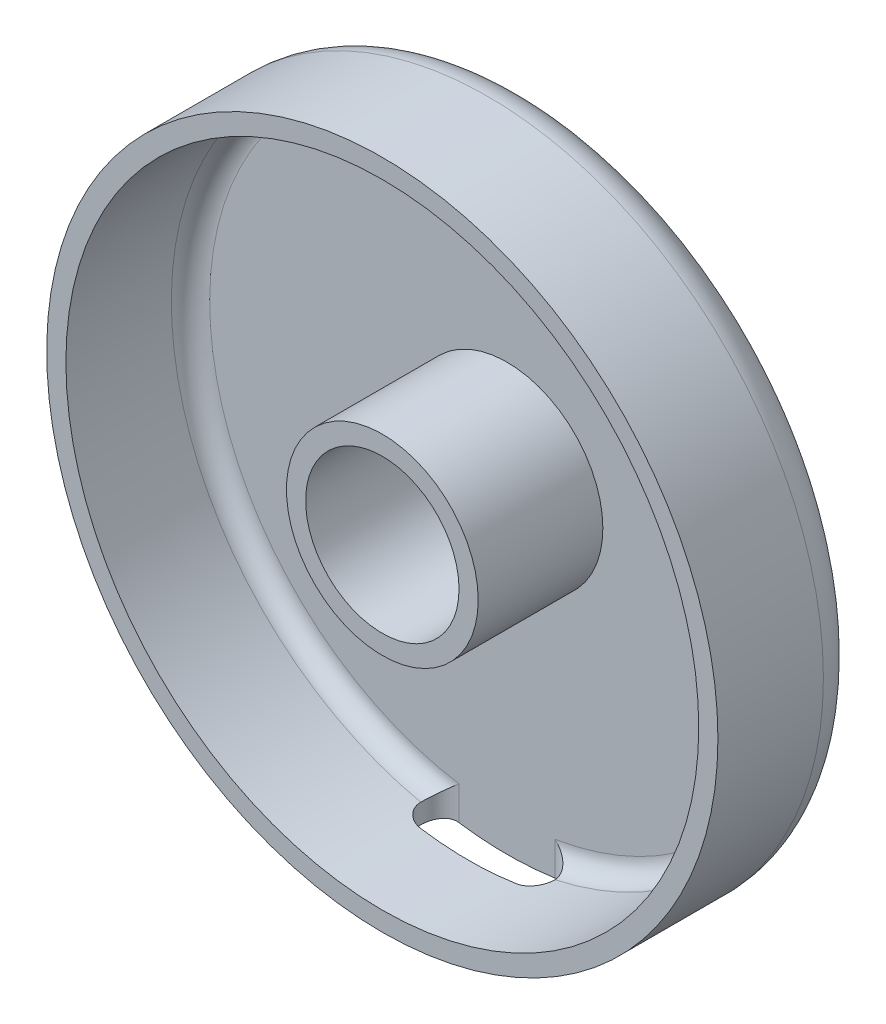
SolidWorks part; units mm, degrees
ref_plane "Alzado" through (0, 0, 0) normal (0, 0, 1) x (1, 0, 0)
ref_plane "Planta" through (0, 0, 0) normal (0, 1, 0) x (1, 0, 0)
ref_plane "Vista lateral" through (0, 0, 0) normal (1, 0, 0) x (0, 0, -1)
sketch "Croquis1" plane through (0, 0, 0) normal (0, 0, 1) x (1, 0, 0)
  circle A0 centre (0, 0) radius 35
  dimension "D1" = 70
extrude "Saliente-Extruir1" add sketch "Croquis1" along normal blind 15
sketch "Croquis2" plane through (0, 0, 15) normal (0, 0, 1) x (1, 0, 0)
  circle A0 centre (0, 0) radius 8
  dimension "D1" = 16
extrude "Cortar-Extruir1" cut sketch "Croquis2" against normal through all
shell "Vaciado1" thickness 2
fillet "Redondeo1" radius 2 1 edges at (33, 0, 2)
fillet "Redondeo2" radius 4 1 edges at (35, 0, 0)
sketch "Croquis3" plane through (0, 0, 0) normal (0, 1, 0) x (1, 0, 0)
  line L0 (-5, -4) -> (5, -4) construction
  line L1 (-5, -2) -> (5, -2)
  line L2 (-5, -6) -> (5, -6)
  line L3 (0, 0) -> (0, -15) construction
  line L4 (-35, -15) -> (35, -15) construction
  line L5 (35, -4) -> (-35, -4) construction
  arc A0 (-5, -2) -> (-5, -6) centre (-5, -4) ccw
  arc A1 (5, -6) -> (5, -2) centre (5, -4) ccw
  point P2 (0, -4)
  dimension "D1" = 2
  dimension "D2" = 10
extrude "Cortar-Extruir2" cut sketch "Croquis3" against normal through all from offset 25
